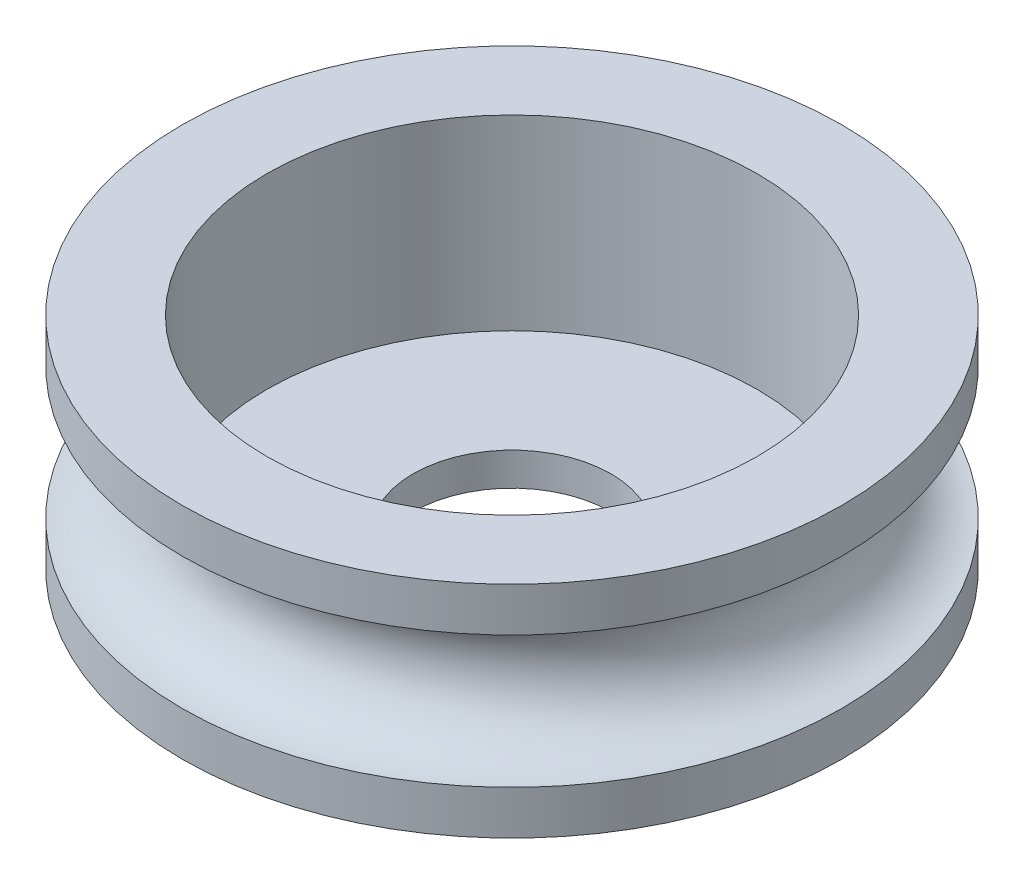
SolidWorks part; units mm, degrees
ref_plane "Plano frontal" through (0, 0, 0) normal (0, 0, 1) x (1, 0, 0)
ref_plane "Plano superior" through (0, 0, 0) normal (0, 1, 0) x (1, 0, 0)
ref_plane "Plano direito" through (0, 0, 0) normal (1, 0, 0) x (0, 0, -1)
sketch "Esboço1" plane through (0, 0, 0) normal (0, 1, 0) x (1, 0, 0)
  circle A0 centre (0, 0) radius 15
  dimension "D1" = 30
extrude "Ressalto-extrusão1" add sketch "Esboço1" along normal blind 10
sketch "Esboço8" plane through (0, 0, 0) normal (0, 0, 1) x (1, 0, 0)
  line L0 (15, 5) -> (-15, 5) construction
  line L1 (15, 0) -> (15, 10) construction
  line L2 (-15, 10) -> (-15, 0) construction
  line L3 (15, 8) -> (15, 2)
  line L4 (0, 0) -> (0, 10) construction
  line L5 (15, 10) -> (-15, 10) construction
  arc A0 (15, 8) -> (15, 2) centre (15, 5) ccw
  point P9 (12, 5)
  dimension "D1" = 6
revolve "Corte-Revolução1" cut sketch "Esboço8" angle 360 about L4
sketch "Esboço9" plane through (0, 10, 0) normal (0, 1, 0) x (1, 0, 0)
  circle A0 centre (0, 0) radius 11.15
  dimension "D1" = 22.3
extrude "Corte-extrusão1" cut sketch "Esboço9" against normal blind 8.5
sketch "Esboço10" plane through (0, 0, 0) normal (0, -1, 0) x (1, 0, 0)
  circle A0 centre (0, 0) radius 4.5
  dimension "D1" = 9
extrude "Corte-extrusão2" cut sketch "Esboço10" against normal through all
